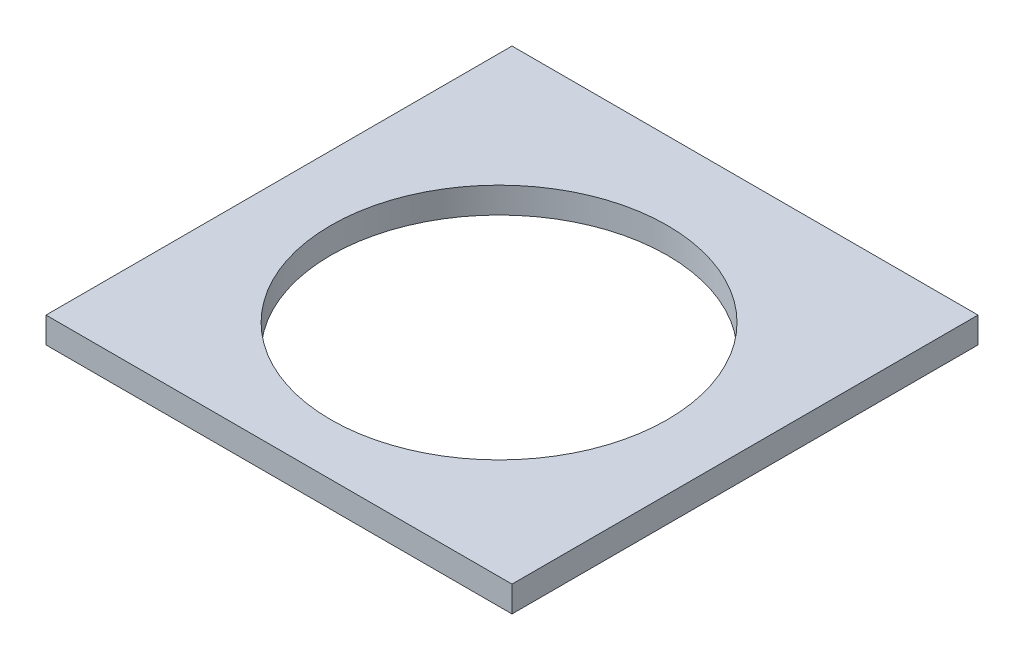
SolidWorks part; units mm, degrees
ref_plane "정면" through (0, 0, 0) normal (0, 0, 1) x (1, 0, 0)
ref_plane "윗면" through (0, 0, 0) normal (0, 1, 0) x (1, 0, 0)
ref_plane "우측면" through (0, 0, 0) normal (1, 0, 0) x (0, 0, -1)
sketch "스케치1" plane through (0, 0, 0) normal (0, 1, 0) x (1, 0, 0)
  line L0 (0, 73.84) -> (0, -73.84) construction
  line L2 (9, -9) -> (-9, -9)
  line L3 (9, -9) -> (9, 9)
  line L4 (9, 9) -> (-9, 9)
  line L5 (-9, -9) -> (-9, 9)
  line L6 (9, -9) -> (-9, 9) construction
  line L7 (9, 9) -> (-9, -9) construction
  point P3 (0, 0)
  dimension "D1" = 18
  dimension "D2" = 18
extrude "보스-돌출1" add sketch "스케치1" along normal blind 8
sketch "스케치5" plane through (0, 0, 0) normal (0, 1, 0) x (1, 0, 0)
  line L0 (-9, 9) -> (-9, -9) construction
  line L1 (-8, 9) -> (8, 9)
  line L2 (-8, 9) -> (-8, -8)
  line L3 (-8, -8) -> (8, -8)
  line L4 (8, 9) -> (8, -8)
  line L5 (9, 9) -> (-9, 9) construction
  dimension "D1" = 16
  dimension "D2" = 1
  dimension "D3" = 17
extrude "컷-돌출6" cut sketch "스케치5" against normal blind 7 from surface at 8 starting at face at (0, 8, 0)
sketch "스케치6" plane through (0, 0, 0) normal (0, 1, 0) x (1, 0, 0)
  line L1 (9, -9) -> (-9, -9)
  line L2 (9, -9) -> (9, 9)
  line L3 (9, 9) -> (-9, 9)
  line L4 (-9, -9) -> (-9, 9)
  line L5 (9, -9) -> (-9, 9) construction
  line L6 (9, 9) -> (-9, -9) construction
  point P0 (0, 0)
extrude "보스-돌출2" add sketch "스케치6" along normal blind 1 from offset 8 separate body
sketch "스케치7" plane through (0, 0, 0) normal (0, 1, 0) x (1, 0, 0)
  line L1 (9, 9) -> (-9, 9) construction
  circle A0 centre (0, -0.5) radius 6.5
  dimension "D1" = 3
  dimension "D2" = 13
extrude "컷-돌출7" cut sketch "스케치7" against normal blind 1 from surface at 9 starting at face at (0, 9, 0)
sketch "스케치11" plane through (0, 0, 0) normal (0, -1, 0) x (1, 0, 0)
  line L4 (-9, 9) -> (-9, -9)
  line L5 (-9, -9) -> (9, -9)
  line L6 (9, -9) -> (9, 9)
  line L7 (9, 9) -> (-9, 9)
  line L8 (-9, 9) -> (-9, -9)
  line L9 (-9, -9) -> (9, -9)
  line L10 (9, -9) -> (9, 9)
  line L11 (9, 9) -> (-9, 9)
  dimension "D1" = 0
extrude "컷-돌출9" cut sketch "스케치11" against normal blind 8
